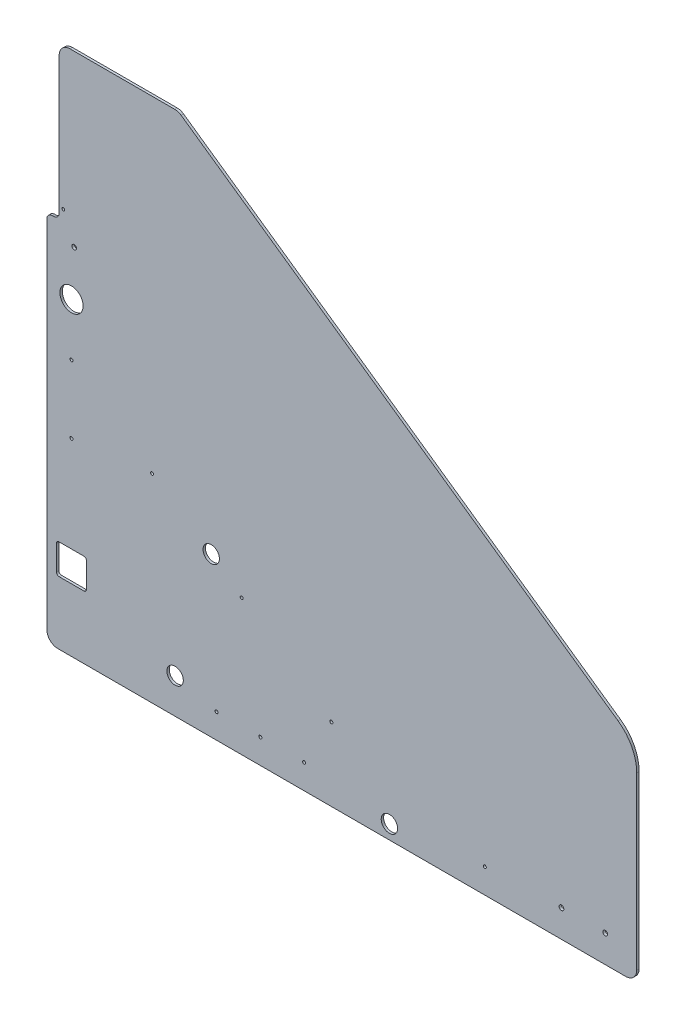
SolidWorks part; units mm, degrees
material "Acrylic (Medium-high impact)"
ref_plane "Front Plane" through (0, 0, 0) normal (0, 0, 1) x (1, 0, 0)
ref_plane "Top Plane" through (0, 0, 0) normal (0, 1, 0) x (1, 0, 0)
ref_plane "Right Plane" through (0, 0, 0) normal (1, 0, 0) x (0, 0, -1)
sketch "Sketch1" plane through (0, 0, 0) normal (0, 0, 1) x (1, 0, 0)
  line L0 (1368.4326, 25.4) -> (1368.4326, 421.5468)
  line L4 (12.7, 863.6) -> (15.875, 863.6)
  line L5 (28.575, 876.3) -> (28.575, 1193.8)
  line L6 (22.225, 209.55) -> (22.225, 152.4)
  line L7 (28.575, 146.05) -> (85.725, 146.05)
  line L8 (92.075, 152.4) -> (92.075, 209.55)
  line L9 (85.725, 215.9) -> (28.575, 215.9)
  line L10 (1343.0326, 0) -> (25.4, 0)
  line L11 (0, 25.4) -> (0, 850.9)
  line L14 (1325.108, 504.7727) -> (311.3603, 1214.6065)
  line L16 (53.975, 1219.2) -> (296.7914, 1219.2)
  arc A0 (0, 25.4) -> (25.4, 0) centre (25.4, 25.4) ccw
  arc A3 (311.3603, 1214.6065) -> (296.7914, 1219.2) centre (296.7914, 1193.8) ccw
  circle A5 centre (794.6898, 32.5628) radius 19.05
  circle A6 centre (381.2769, 367.8301) radius 19.05
  arc A11 (1343.0326, 0) -> (1368.4326, 25.4) centre (1343.0326, 25.4) ccw
  arc A20 (22.225, 152.4) -> (28.575, 146.05) centre (28.575, 152.4) ccw
  arc A21 (85.725, 146.05) -> (92.075, 152.4) centre (85.725, 152.4) ccw
  arc A22 (92.075, 209.55) -> (85.725, 215.9) centre (85.725, 209.55) ccw
  arc A23 (28.575, 215.9) -> (22.225, 209.55) centre (28.575, 209.55) ccw
  circle A25 centre (57.1501, 717.55) radius 26.9875
  arc A26 (12.7, 863.6) -> (0, 850.9) centre (12.7, 850.9) ccw
  circle A27 centre (297.4823, 81.5975) radius 19.05
  arc A28 (15.875, 863.6) -> (28.575, 876.3) centre (15.875, 876.3) ccw
  circle A30 centre (57.1501, 595.9731) radius 3.556
  circle A31 centre (57.1501, 438.15) radius 3.556
  circle A32 centre (243.943, 461.1079) radius 3.556
  circle A33 centre (452.0076, 315.4195) radius 3.556
  circle A34 centre (660.0722, 169.7311) radius 3.556
  circle A35 centre (393.7, 57.15) radius 3.556
  circle A36 centre (495.3, 57.15) radius 3.556
  circle A37 centre (596.9, 57.15) radius 3.556
  circle A38 centre (1016, 57.15) radius 3.556
  arc A39 (53.975, 1219.2) -> (28.575, 1193.8) centre (53.975, 1193.8) ccw
  circle A40 centre (1193.8076, 63.5) radius 5.5562
  circle A41 centre (1295.4076, 63.5) radius 5.5562
  circle A43 centre (38.1, 889) radius 3.175
  arc A44 (1325.108, 504.7727) -> (1368.4326, 421.5468) centre (1266.8326, 421.5468) cw
  circle A45 centre (63.5, 825.5) radius 5.3578
  point P31 (0, 0)
  point P45 (304.8, 1219.2)
  point P48 (0, 1219.2)
  point P57 (1368.4326, 0)
  dimension "D4" = 7.112
  dimension "D5" = 57.1501
  dimension "D20" = 38.1
  dimension "D21" = 53.975
  dimension "D30" = 6.35
  dimension "D31" = 25.4
  dimension "D33" = 38.1
  dimension "D35" = 83.7946
  dimension "D37" = 38.1
  dimension "D41" = 63.5
  dimension "D42" = 10.7156
  dimension "D44" = 609.6
  dimension "D45" = 25.4
  dimension "D46" = 101.6
  dimension "D49" = 12.7
  dimension "D50" = 25.4
  dimension "D43" = 11.1125
  dimension "D52" = 6.35
  dimension "D39" = 101.6
  dimension "D1" = 1219.2
  dimension "D3" = 304.8
  dimension "D6" = 57.15
  dimension "D7" = 157.8231
  dimension "D8" = 297.4823
  dimension "D9" = 96.2177
  dimension "D10" = 101.6
  dimension "D11" = 101.6
  dimension "D12" = 419.1
  dimension "D13" = 22.225
  dimension "D14" = 69.85
  dimension "D15" = 69.85
  dimension "D16" = 146.05
  dimension "D17" = 222.25
  dimension "D18" = 121.5769
  dimension "D19" = 501.65
  dimension "D22" = 1368.4326
  dimension "D23" = 243.943
  dimension "D24" = 461.1079
  dimension "D25" = 315.4195
  dimension "D26" = 452.0076
  dimension "D27" = 169.7311
  dimension "D28" = 660.0722
  dimension "D29" = 81.5975
  dimension "D32" = 221.3102
  dimension "D34" = 24.5872
  dimension "D36" = 286.2326
  dimension "D38" = 125
  dimension "D40" = 63.5
  dimension "D47" = 28.575
  dimension "D48" = 355.6
  dimension "D51" = 73.025
  dimension "D53" = 9.525
  dimension "D54" = 25.4
extrude "Boss-Extrude1" add sketch "Sketch1" along normal blind 5.588
